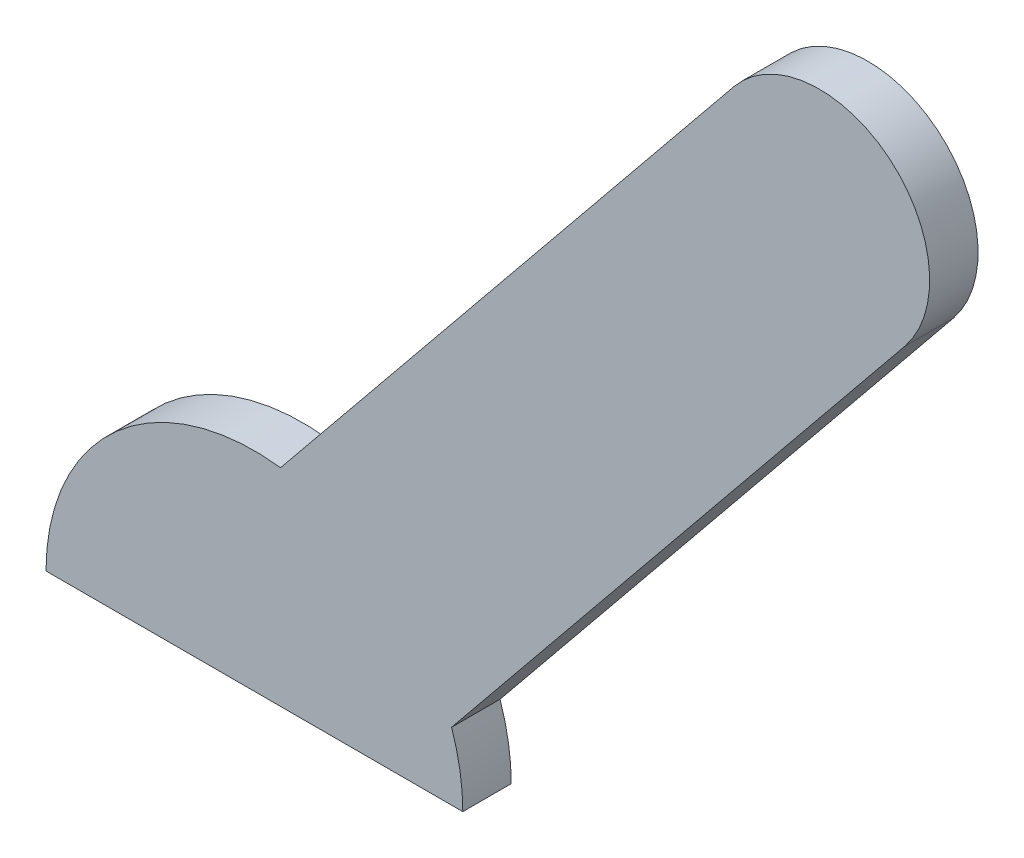
SolidWorks part; units mm, degrees
ref_plane "Front Plane" through (0, 0, 0) normal (0, 0, 1) x (1, 0, 0)
ref_plane "Top Plane" through (0, 0, 0) normal (0, 1, 0) x (1, 0, 0)
ref_plane "Right Plane" through (0, 0, 0) normal (1, 0, 0) x (0, 0, -1)
sketch "Sketch1" plane through (0, 0, 0) normal (0, 0, 1) x (1, 0, 0)
  line L0 (0, 0) -> (29.6196, 36.3729) construction
  line L3 (1.3716, 10.8397) -> (25.1368, 40.0234)
  line L8 (10.3372, 3.5388) -> (34.1024, 32.7225)
  line L9 (-10.9262, 0) -> (10.9262, 0)
  line L10 (0, 0) -> (36.5473, 0) construction
  line L11 (0, 0) -> (0, 29.1314) construction
  line L12 (29.6196, 36.3729) -> (40.937, 50.2707) construction
  line L13 (29.6196, 36.3729) -> (14.8098, 48.294) construction
  arc A3 (34.1024, 32.7225) -> (25.1368, 40.0234) centre (29.6196, 36.3729) ccw
  arc A4 (-10.9262, 0) -> (10.9262, 0) centre (0, 0) cw
  text T0 "N1"
  text T1 "N2"
  text T2 "A1"
  text T3 "A2"
  point P3 (14.8098, 18.1865)
  point P17 (0, 0)
  point P20 (0, 0)
  point P21 (0, 0)
extrude "Boss-Extrude2" add sketch "Sketch1" along normal blind 2.54
sketch "Sketch2" plane through (0, 0, 0) normal (0, 0, 1) x (1, 0, 0)
  line L0 (14.8098, 18.1865) -> (17.1054, 16.3171)
  line L1 (14.8098, 18.1865) -> (16.1669, 18.3253)
  line L2 (14.8098, 18.1865) -> (14.9487, 16.8294)
  line L3 (0, 0) -> (29.6196, 36.3729) construction
  text T0 "N"
  text T1 "A_com"
  text T2 "A"
  point P1 (0, 0)
  point P5 (0, 0)
  point P8 (0, 0)
  point P11 (14.8098, 16.8223)
  point P12 (0, 0)
  point P13 (16.1178, 18.2747)
  dimension "D1" = 90
  dimension "D2" = 45
sketch "Sketch4" plane through (0, 0, 0) normal (0, 0, -1) x (-1, 0, 0)
  line L2 (0, 0) -> (-36.5473, 0) construction
  line L3 (10.9262, 0) -> (-10.9262, 0) construction
  line L4 (0, 0) -> (-29.6196, 36.3729) construction
  dimension "D1" = 50.843
  dimension "D2" = 46.9075
equation "\"alpha1\"=50.843"
